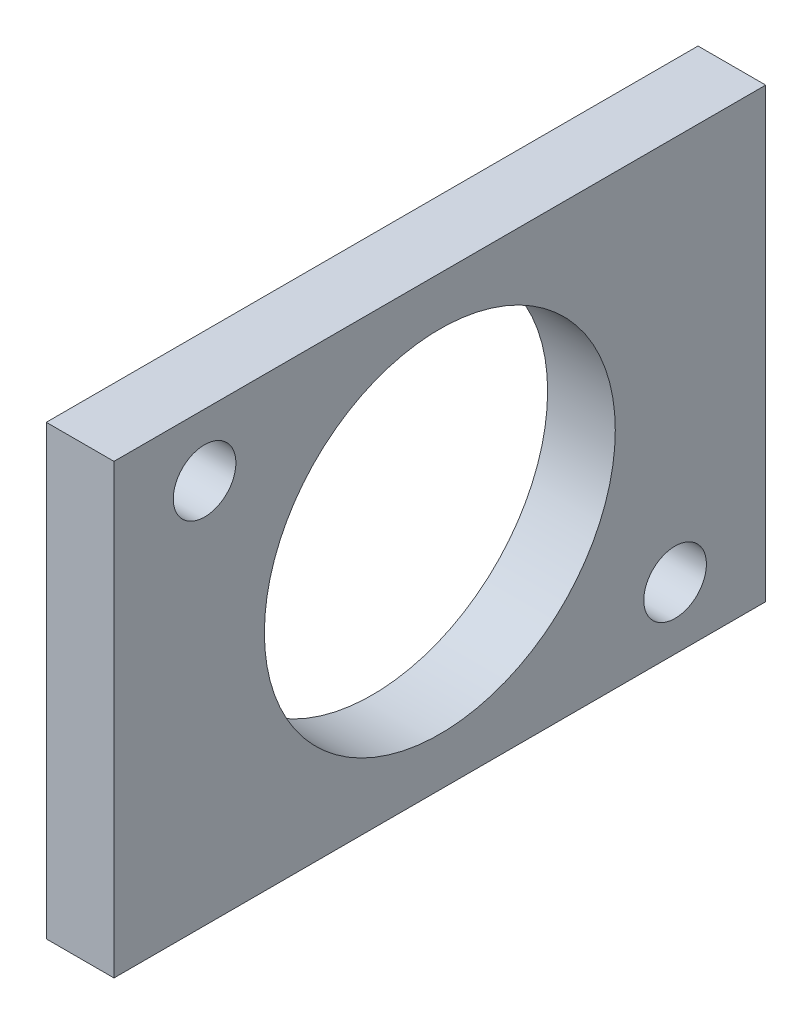
SolidWorks part; units mm, degrees
ref_plane "Alzado" through (0, 0, 0) normal (0, 0, 1) x (1, 0, 0)
ref_plane "Planta" through (0, 0, 0) normal (0, 1, 0) x (1, 0, 0)
ref_plane "Vista lateral" through (0, 0, 0) normal (1, 0, 0) x (0, 0, -1)
sketch "Croquis2" plane through (0, 0, 0) normal (1, 0, 0) x (0, 0, -1)
  line L1 (-26, 17.85) -> (26, 17.85)
  line L2 (-26, 17.85) -> (-26, -17.85)
  line L3 (-26, -17.85) -> (26, -17.85)
  line L4 (26, 17.85) -> (26, -17.85)
  line L5 (-26, 17.85) -> (26, -17.85) construction
  line L6 (-26, -17.85) -> (26, 17.85) construction
  point P0 (0, 0)
  dimension "D1" = 52
  dimension "D2" = 35.7
extrude "Saliente-Extruir1" add sketch "Croquis2" along normal blind 5.4
sketch "Croquis3" plane through (5.4, 0, 0) normal (1, 0, 0) x (0, 0, -1)
  circle A2 centre (0, 0) radius 14
  circle A3 centre (-18.7709, 12.8869) radius 2.5
  circle A4 centre (18.7709, -12.8869) radius 2.5
extrude "Cortar-Extruir2" cut sketch "Croquis3" against normal blind 5.4
